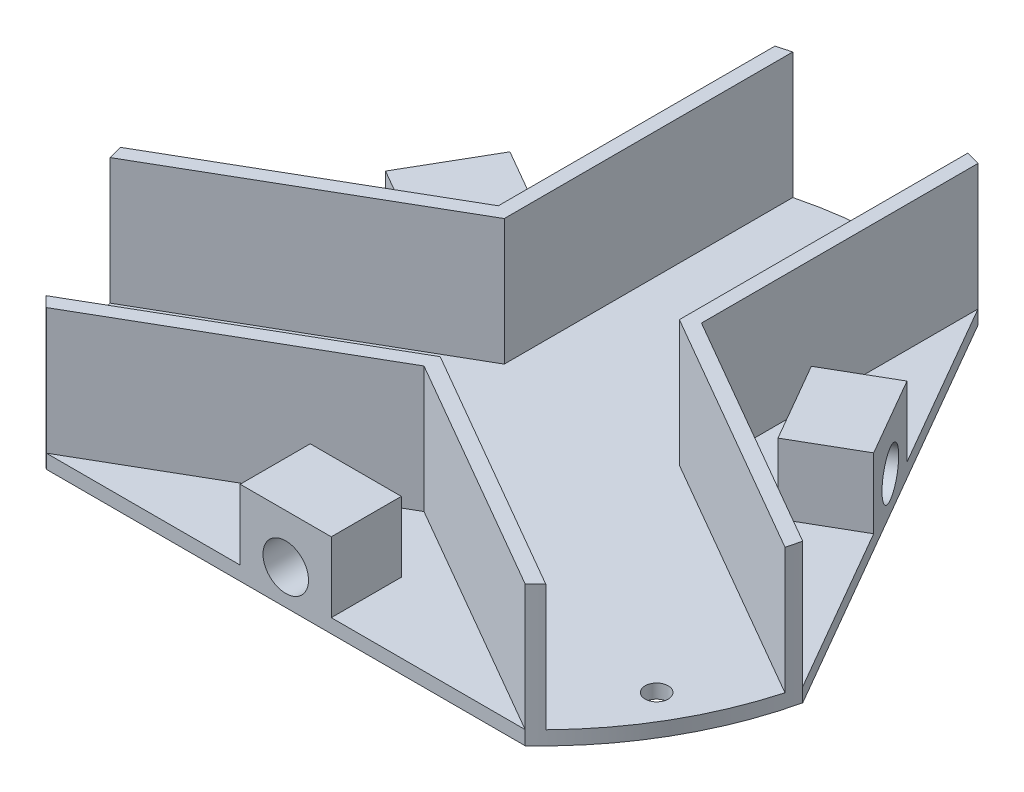
SolidWorks part; units mm, degrees
ref_plane "Front Plane" through (0, 0, 0) normal (0, 0, 1) x (1, 0, 0)
ref_plane "Top Plane" through (0, 0, 0) normal (0, 1, 0) x (1, 0, 0)
ref_plane "Right Plane" through (0, 0, 0) normal (1, 0, 0) x (0, 0, -1)
sketch "Sketch1" plane through (0, 0, 0) normal (0, 1, 0) x (1, 0, 0)
  line L0 (14.5, 8.3716) -> (48.6905, -11.3683) construction
  line L1 (-14.5, 0) -> (14.5, 0) construction
  line L2 (-14.5, 0) -> (-14.5, 47.8513) construction
  line L3 (0, 0) -> (-7.25, -12.5574) construction
  line L4 (14.5, 0) -> (14.5, 47.8513) construction
  line L5 (-7.25, -12.5574) -> (34.1905, -36.483) construction
  line L6 (7.25, -12.5574) -> (-34.1905, -36.483) construction
  line L7 (7.25, -12.5574) -> (0, 0) construction
  line L8 (-14.5, 8.3716) -> (-48.6905, -11.3683) construction
  line L9 (14.5, 47.8513) -> (48.6905, -11.3683)
  line L10 (-14.5, 47.8513) -> (-48.6905, -11.3683)
  line L11 (-34.1905, -36.483) -> (34.1905, -36.483)
  line L12 (-38.9711, -22.5) -> (0, 0) construction
  line L13 (0, 0) -> (0, 45) construction
  arc A0 (-48.6905, -11.3683) -> (-34.1905, -36.483) centre (0, 0) ccw
  arc A1 (14.5, 47.8513) -> (-14.5, 47.8513) centre (0, 0) ccw
  arc A2 (34.1905, -36.483) -> (48.6905, -11.3683) centre (0, 0) ccw
  circle A3 centre (0, 45) radius 1.65
  circle A4 centre (38.9711, -22.5) radius 1.65
  circle A5 centre (-38.9711, -22.5) radius 1.65
  point P17 (0, 0)
  point P23 (0, 0)
  dimension "D1" = 100
  dimension "D4" = 3.3
  dimension "D2" = 29
  dimension "D5" = 45
  dimension "D7" = 120
  dimension "D3" = 3
  dimension "D6" = 3
extrude "Boss-Extrude1" add sketch "Sketch1" along normal blind 2
sketch "Sketch2" plane through (0, 2, 0) normal (0, 1, 0) x (1, 0, 0)
  line L0 (-14.5, 47.8513) -> (-14.5, 8.3716)
  line L1 (-14.5, 8.3716) -> (-48.6905, -11.3683)
  line L2 (14.5, 47.8513) -> (14.5, 8.3716)
  line L3 (14.5, 8.3716) -> (48.6905, -11.3683)
  line L4 (-34.1905, -36.483) -> (0, -16.7432)
  line L5 (0, -16.7432) -> (34.1905, -36.483)
  line L6 (-48.1763, -13.3808) -> (-12.5, 7.2169)
  line L7 (-12.5, 7.2169) -> (-12.5, 48.4123)
  line L8 (12.5, 48.4123) -> (12.5, 7.2169)
  line L9 (12.5, 7.2169) -> (48.1763, -13.3808)
  line L10 (35.6763, -35.0315) -> (0, -14.4338)
  line L11 (0, -14.4338) -> (-35.6763, -35.0315)
  arc A0 (-48.6905, -11.3683) -> (-48.1763, -13.3808) centre (0, 0) ccw
  arc A1 (14.5, 47.8513) -> (12.5, 48.4123) centre (0, 0) ccw
  arc A2 (34.1905, -36.483) -> (35.6763, -35.0315) centre (0, 0) ccw
  arc A3 (-35.6763, -35.0315) -> (-34.1905, -36.483) centre (0, 0) ccw
  arc A4 (48.1763, -13.3808) -> (48.6905, -11.3683) centre (0, 0) ccw
  arc A5 (-12.5, 48.4123) -> (-14.5, 47.8513) centre (0, 0) ccw
  dimension "D1" = 120
  dimension "D2" = 120
  dimension "D3" = 120
  dimension "D4" = 2
  dimension "D5" = 2
  dimension "D6" = 2
  dimension "D7" = 2
  dimension "D8" = 2
  dimension "D9" = 2
extrude "Boss-Extrude2" add sketch "Sketch2" along normal blind 18
sketch "Sketch3" plane through (31.5952, 0, -18.2415) normal (0.866, 0, -0.5) x (-0.5, 0, -0.866)
  line L0 (0, 20) -> (0, 2) construction
  line L1 (-11.2573, -3) -> (9.9508, -3) construction
  line L2 (-34.1905, 0) -> (34.1905, 0) construction
  line L3 (-34.1905, 2) -> (34.1905, 2) construction
  line L4 (-6.5, 2) -> (6.5, 2)
  line L5 (-6.5, 2) -> (-6.5, 12)
  line L6 (-6.5, 12) -> (6.5, 12)
  line L7 (6.5, 2) -> (6.5, 12)
  circle A0 centre (0, 5) radius 8 construction
  circle A1 centre (0, 5) radius 3.25 construction
  dimension "D1" = 16
  dimension "D6" = 6.5
  dimension "D2" = 3
  dimension "D3" = 13
  dimension "D4" = 6.5
  dimension "D5" = 10
extrude "Boss-Extrude3" add sketch "Sketch3" against normal blind 10
sketch "Sketch4" plane through (31.5952, 0, -18.2415) normal (0.866, 0, -0.5) x (-0.5, 0, -0.866)
  line L0 (-16.3795, -3) -> (49983.6205, -3) construction
  line L1 (-34.1905, 0) -> (34.1905, 0) construction
  circle A0 centre (0, 5) radius 8 construction
  circle A1 centre (0, 5) radius 3.25
  dimension "D1" = 6.5
  dimension "D2" = 16
  dimension "D3" = 3
extrude "Cut-Extrude1" cut sketch "Sketch4" against normal up to surface (10 mm away) up to face at (22.935, 7, -13.2415)
pattern_circular "CirPattern1" count 3 every 120 about axis through (0, 0, 0) along (0, 1, 0) of "Boss-Extrude3", "Cut-Extrude1"
